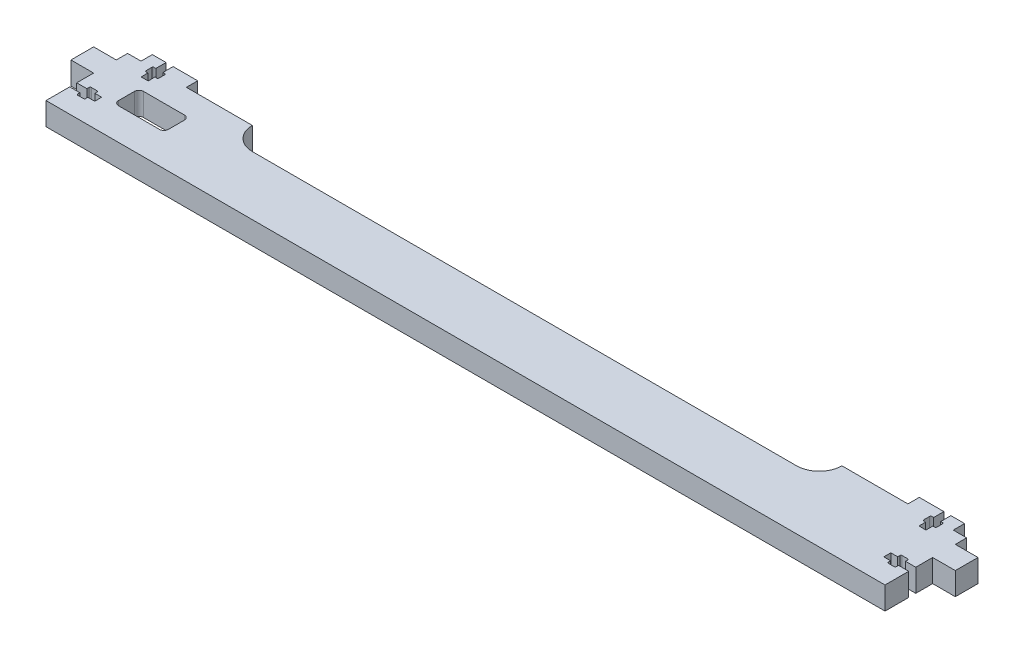
SolidWorks part; units mm, degrees
ref_plane "Front Plane" through (0, 0, 0) normal (0, 0, 1) x (1, 0, 0)
ref_plane "Top Plane" through (0, 0, 0) normal (0, 1, 0) x (1, 0, 0)
ref_plane "Right Plane" through (0, 0, 0) normal (1, 0, 0) x (0, 0, -1)
sketch "Sketch1" plane through (0, 0, 0) normal (0, 1, 0) x (1, 0, 0)
  line L0 (0, 18) -> (0, -18) construction
  line L1 (-185, 18) -> (0, 18)
  line L2 (-185, 18) -> (-185, 13)
  line L3 (-185, -18) -> (0, -18)
  line L4 (0, 18) -> (0, -18)
  line L5 (-185, 18) -> (0, 0) construction
  line L6 (-185, -18) -> (0, 0) construction
  line L7 (-185, 13) -> (-195, 13)
  line L8 (-195, 13) -> (-195, 3)
  line L9 (-195, 3) -> (-185, 3)
  line L10 (-185, 3) -> (-185, -18)
  point P0 (0, 0)
  dimension "D6" = 10
  dimension "D7" = 10
  dimension "D1" = 185
  dimension "D2" = 36
  dimension "D4" = 5
  dimension "D9" = 18
extrude "MainShape" add sketch "Sketch1" along normal blind 10
sketch "Sketch15" plane through (0, 10, 0) normal (0, 1, 0) x (1, 0, 0)
  line L0 (-185, 18) -> (0, 18) construction
  line L1 (-159.1, 23) -> (-179.1, 23)
  line L2 (-159.1, 23) -> (-159.1, 13)
  line L3 (-159.1, 13) -> (-179.1, 13)
  line L4 (-179.1, 23) -> (-179.1, 13)
  line L5 (-159.1, 23) -> (-179.1, 13) construction
  line L6 (-159.1, 13) -> (-179.1, 23) construction
  line L7 (-185, 18) -> (-185, 13) construction
  point P0 (-169.1, 18)
  dimension "D1" = 20
  dimension "D2" = 5
  dimension "D3" = 15.9
extrude "Boss-Extrude4" add sketch "Sketch15" against normal through all
sketch "Sketch2" plane through (0, 10, 0) normal (0, 1, 0) x (1, 0, 0)
  line L0 (-171.5, 23) -> (-171.5, 12) construction
  line L2 (-173.05, 23) -> (-173.05, 18.5)
  line L3 (-173.05, 18.5) -> (-173.85, 18.5)
  line L4 (-174.35, 18) -> (-174.35, 15.5)
  line L5 (-173.85, 15) -> (-173.05, 15)
  line L6 (-173.05, 15) -> (-173.05, 12)
  line L7 (-173.05, 12) -> (-169.95, 12)
  line L8 (-185, 18) -> (-185, 13) construction
  line L9 (-173.05, 23) -> (-169.95, 23)
  line L10 (-169.95, 15) -> (-169.95, 12)
  line L11 (-169.15, 15) -> (-169.95, 15)
  line L12 (-168.65, 18) -> (-168.65, 15.5)
  line L13 (-169.95, 18.5) -> (-169.15, 18.5)
  line L14 (-169.95, 23) -> (-169.95, 18.5)
  line L16 (-185, -6) -> (-174, -6) construction
  line L17 (-159.1, 23) -> (-179.1, 23) construction
  line L50 (-185, 3) -> (-185, -18) construction
  line L51 (-174, -7.55) -> (-174, -4.45)
  line L52 (-174, -4.45) -> (-177, -4.45)
  line L53 (-177, -4.45) -> (-177, -3.5)
  line L54 (-177.5, -3) -> (-180, -3)
  line L55 (-180.5, -3.5) -> (-180.5, -4.45)
  line L56 (-180.5, -4.45) -> (-185, -4.45)
  line L57 (-185, -4.45) -> (-185, -7.55)
  line L58 (-195, 13) -> (-195, 3) construction
  line L59 (-180.5, -7.55) -> (-185, -7.55)
  line L60 (-180.5, -8.5) -> (-180.5, -7.55)
  line L61 (-177.5, -9) -> (-180, -9)
  line L62 (-177, -7.55) -> (-177, -8.5)
  line L63 (-174, -7.55) -> (-177, -7.55)
  arc A0 (-174.35, 15.5) -> (-173.85, 15) centre (-173.85, 15.5) ccw
  arc A1 (-173.85, 18.5) -> (-174.35, 18) centre (-173.85, 18) ccw
  arc A2 (-169.15, 18.5) -> (-168.65, 18) centre (-169.15, 18) cw
  arc A3 (-168.65, 15.5) -> (-169.15, 15) centre (-169.15, 15.5) cw
  arc A16 (-177, -3.5) -> (-177.5, -3) centre (-177.5, -3.5) ccw
  arc A17 (-180, -3) -> (-180.5, -3.5) centre (-180, -3.5) ccw
  arc A18 (-180, -9) -> (-180.5, -8.5) centre (-180, -8.5) cw
  arc A19 (-177, -8.5) -> (-177.5, -9) centre (-177.5, -8.5) cw
  point P14 (-174.35, 15)
  point P17 (-174.35, 18.5)
  point P28 (-168.65, 18.5)
  point P29 (-168.65, 15)
  point P34 (-195, 8)
  point P45 (-177, -3)
  point P48 (-180.5, -3)
  dimension "D8" = 0.5
  dimension "D16" = 0.5
  dimension "D1" = 11
  dimension "D2" = 1.55
  dimension "D3" = 1.55
  dimension "D5" = 2.85
  dimension "D6" = 3.5
  dimension "D7" = 13.5
  dimension "D9" = 11
  dimension "D10" = 8
  dimension "D11" = 3.5
  dimension "D12" = 3
  dimension "D13" = 1.55
  dimension "D14" = 1.55
  dimension "D15" = 14
  dimension "D4" = 8
extrude "ScrewSlots" cut sketch "Sketch2" against normal through all
mirror "Mirror1" about plane through (0, 0, 0) normal (1, 0, 0) of "Boss-Extrude4", "ScrewSlots", "MainShape"
sketch "Sketch6" plane through (0, 10, 0) normal (0, 1, 0) x (1, 0, 0)
  line L0 (0, -18) -> (0, -48) construction
  line L2 (-185, -18) -> (185, -18) construction
  line L3 (90, -48) -> (-90, -48)
  line L4 (-90, -48) -> (-120, -18)
  line L5 (90, -48) -> (120, -18)
  line L6 (-120, -18) -> (120, -18)
  dimension "D1" = 135
  dimension "D2" = 30
  dimension "D3" = 90
extrude "Boss-Extrude1" [suppressed] add sketch "Sketch6" against normal through all
sketch "Sketch8" plane through (0, 10, 0) normal (0, 1, 0) x (1, 0, 0)
  line L0 (-71.5, 4.8833) -> (-77.5, 4.8833) construction
  line L1 (-77, -1.6167) -> (-72, -1.6167)
  line L2 (-78, -0.6167) -> (-78, 4.3833)
  line L3 (-77, 5.3833) -> (-72, 5.3833)
  line L4 (-71, -0.6167) -> (-71, 4.3833)
  line L5 (-78, -1.6167) -> (-71, 5.3833) construction
  line L6 (-78, 5.3833) -> (-71, -1.6167) construction
  line L7 (-71.5, -1.1167) -> (-71.5, 4.8833) construction
  circle A0 centre (-74.5, -34.7667) radius 6.5
  circle A1 centre (-74.5, -15.8167) radius 5.5
  arc A2 (-77, -1.6167) -> (-78, -0.6167) centre (-77, -0.6167) cw
  circle A3 centre (-74.5, -34.7667) radius 6 construction
  circle A4 centre (-74.5, -15.8167) radius 3.5 construction
  arc A5 (-72, -1.6167) -> (-71, -0.6167) centre (-72, -0.6167) ccw
  arc A6 (-72, 5.3833) -> (-71, 4.3833) centre (-72, 4.3833) cw
  arc A7 (-78, 4.3833) -> (-77, 5.3833) centre (-77, 4.3833) cw
  point P6 (-74.5, 1.8833)
  dimension "D1" = 0.5
  dimension "D2" = 2
  dimension "D3" = 0.5
  dimension "D5" = 1
  dimension "D4" = 0.5
extrude "Cut-Extrude2" [suppressed] cut sketch "Sketch8" against normal through all
sketch "Sketch7" plane through (0, 10, 0) normal (0, 1, 0) x (1, 0, 0)
  circle A0 centre (60.5, -43.0167) radius 1.45
  circle A1 centre (-84.5, -43.0167) radius 1.45
  circle A2 centre (-84.5, 6.4833) radius 1.45
  circle A3 centre (60.5, 6.4833) radius 1.45
  dimension "D1" = 2.9
  dimension "D2" = 2.9
  dimension "D3" = 2.9
  dimension "D4" = 2.9
extrude "Cut-Extrude1" [suppressed] cut sketch "Sketch7" against normal through all
sketch "Sketch9" plane through (0, 10, 0) normal (0, 1, 0) x (1, 0, 0)
  line L0 (0, 7.2333) -> (0, -32.7667) construction
  line L1 (48.5, 7.2333) -> (-48.5, 7.2333) construction
  line L2 (-48.5, -32.7667) -> (48.5, -32.7667) construction
  line L3 (-48.5, -12.7667) -> (48.5, -12.7667) construction
  line L4 (-48.5, 7.2333) -> (-48.5, -32.7667) construction
  line L5 (48.5, -32.7667) -> (48.5, 7.2333) construction
  line L7 (-49, -33.2667) -> (49, -33.2667)
  line L8 (-49, -33.2667) -> (-49, 7.7333)
  line L9 (-49, 7.7333) -> (49, 7.7333)
  line L10 (49, -33.2667) -> (49, 7.7333)
  line L11 (-49, -33.2667) -> (49, 7.7333) construction
  line L12 (-49, 7.7333) -> (49, -33.2667) construction
  point P12 (0, -12.7667)
  dimension "D1" = 0.5
  dimension "D2" = 0.5
extrude "Cut-Extrude3" [suppressed] cut sketch "Sketch9" against normal through all and the other way through all
sketch "Sketch10" plane through (0, 10, 0) normal (0, 1, 0) x (1, 0, 0)
  line L0 (20, -39.2667) -> (20, -40.7667) construction
  line L1 (40, -39.2667) -> (0, -39.2667) construction
  line L2 (0, -40.7667) -> (40, -40.7667) construction
  line L3 (0, -40.0167) -> (40, -40.0167) construction
  line L4 (0, -39.2667) -> (0, -40.7667) construction
  line L5 (40, -40.7667) -> (40, -39.2667) construction
  line L7 (-0.2, -40.9667) -> (40.2, -40.9667)
  line L8 (-0.2, -40.9667) -> (-0.2, -39.0667)
  line L9 (-0.2, -39.0667) -> (40.2, -39.0667)
  line L10 (40.2, -40.9667) -> (40.2, -39.0667)
  line L11 (-0.2, -40.9667) -> (40.2, -39.0667) construction
  line L12 (-0.2, -39.0667) -> (40.2, -40.9667) construction
  point P12 (20, -40.0167)
  dimension "D1" = 0.2
  dimension "D2" = 0.2
extrude "Cut-Extrude4" [suppressed] cut sketch "Sketch10" against normal through all
sketch "Sketch12" [suppressed] plane through (0, 0, 0) normal (0, -1, 0) x (-1, 0, 0)
  line L1 (81.4, -9.8167) -> (67.6, -9.8167)
  line L2 (81.4, -9.8167) -> (81.4, -21.8167)
  line L3 (81.4, -21.8167) -> (67.6, -21.8167)
  line L4 (67.6, -9.8167) -> (67.6, -21.8167)
  line L5 (81.4, -9.8167) -> (67.6, -21.8167) construction
  line L6 (81.4, -21.8167) -> (67.6, -9.8167) construction
  point P0 (74.5, -15.8167)
  dimension "D1" = 13.8
  dimension "D2" = 12
extrude "PotentiometerAdjustment" [suppressed] cut sketch "Sketch12" against normal through all
sketch "Sketch11" plane through (0, 0, 0) normal (0, -1, 0) x (1, 0, 0)
  line L1 (-149, -7) -> (-167, -7)
  line L2 (-147, -5) -> (-147, 2)
  line L3 (-149, 4) -> (-167, 4)
  line L4 (-169, -5) -> (-169, 2)
  line L5 (-147, -7) -> (-169, 4) construction
  line L6 (-147, 4) -> (-169, -7) construction
  line L7 (173.05, -12) -> (169.95, -12) construction
  line L8 (-174, 7.55) -> (-174, 4.45) construction
  arc A0 (-147, 2) -> (-149, 4) centre (-149, 2) ccw
  arc A1 (-167, 4) -> (-169, 2) centre (-167, 2) ccw
  arc A2 (-167, -7) -> (-169, -5) centre (-167, -5) cw
  arc A3 (-149, -7) -> (-147, -5) centre (-149, -5) ccw
  point P0 (-158, -1.5)
  dimension "D3" = 2
  dimension "D1" = 22
  dimension "D2" = 11
  dimension "D4" = 5
  dimension "D5" = 5
extrude "LCDCableCutout" cut sketch "Sketch11" against normal through all
sketch "Sketch13" plane through (0, 10, 0) normal (0, 1, 0) x (1, 0, 0)
  line L0 (0, 18) -> (0, -18) construction
  line L1 (-169.95, 18) -> (169.95, 18) construction
  line L2 (-185, -18) -> (185, -18) construction
  line L3 (120, 18) -> (-120, 18) construction
  line L4 (120, 8) -> (-120, 8)
  line L5 (120, 28) -> (-120, 28)
  arc A0 (120, 8) -> (120, 28) centre (120, 18) ccw
  arc A1 (-120, 28) -> (-120, 8) centre (-120, 18) ccw
  point P8 (0, 18)
  dimension "D2" = 120
  dimension "D1" = 10
extrude "Cut-Extrude5" cut sketch "Sketch13" against normal through all
sketch "Sketch14" plane through (0, 10, 0) normal (0, 1, 0) x (1, 0, 0)
  line L1 (-169.95, 18) -> (169.95, 18) construction
  line L3 (-156.5, 18) -> (-156.5, 28) construction
  line L4 (-161.5, 18) -> (-151.5, 18)
  line L5 (-161.5, 18) -> (-161.5, 28)
  line L6 (-161.5, 28) -> (-151.5, 28)
  line L7 (-151.5, 18) -> (-151.5, 28)
  line L8 (-173.05, 12) -> (-169.95, 12) construction
  line L9 (154, 18) -> (154, 28) construction
  line L10 (149, 18) -> (149, 28)
  line L11 (159, 28) -> (149, 28)
  line L12 (159, 18) -> (159, 28)
  line L13 (159, 18) -> (149, 18)
  point P12 (-171.5, 12)
  dimension "D1" = 10
  dimension "D2" = 10
  dimension "D3" = 15
extrude "Boss-Extrude3" [suppressed] add sketch "Sketch14" against normal through all
equation "\"Y-ROD-SPACING\"=75"
equation "\"Y-BED-OFFSET\"=2"
equation "\"Y-BED-ROD-INSET\"=3.5"
equation "\"T-SLOT-NUT-FILLET-RADIUS\"=0.5"
equation "\"T-SLOT-SCREW-SHAFT-RADIUS\"=1.55"
equation "\"T-SLOT-SCREW-SHAFT-CUTOUT-LENGTH\"=11"
equation "\"T-SLOT-NUT-DEPTH\"=3.5"
equation "\"T-SLOT-NUT-WIDTH\"=2.85"
equation "\"T-SLOT-NUT-END-DISTANCE\"=8"
equation "\"ACRYLIC-TAB-CUTOUT-SIZE\"=\"ACRYLIC-THICKNESS\"+\"ACRYLIC-TAB-TOLERANCE\"*2"
equation "\"ACRYLIC-M3-HOLE\"=2.9"
equation "\"SMOOTHROD-CAP-SCREW-DISTANCE\"=20"
equation "\"D2@Sketch2\"=\"T-SLOT-SCREW-SHAFT-RADIUS\""
equation "\"D1@Sketch2\"=\"T-SLOT-SCREW-SHAFT-CUTOUT-LENGTH\""
equation "\"D6@Sketch2\"=\"T-SLOT-NUT-DEPTH\""
equation "\"D5@Sketch2\"=\"T-SLOT-NUT-WIDTH\""
equation "\"D3@Sketch2\"=\"T-SLOT-SCREW-SHAFT-RADIUS\""
equation "\"D8@Sketch2\"=\"T-SLOT-NUT-FILLET-RADIUS\""
equation "\"D4@Sketch2\"=\"T-SLOT-NUT-END-DISTANCE\""
equation "\"D11@Sketch2\"=\"T-SLOT-NUT-DEPTH\""
equation "\"D10@Sketch2\"=\"T-SLOT-NUT-END-DISTANCE\""
equation "\"D13@Sketch2\"=\"T-SLOT-SCREW-SHAFT-RADIUS\""
equation "\"D14@Sketch2\"=\"T-SLOT-SCREW-SHAFT-RADIUS\""
equation "\"D16@Sketch2\"=\"T-SLOT-NUT-FILLET-RADIUS\""
equation "\"D9@Sketch2\"=\"T-SLOT-SCREW-SHAFT-CUTOUT-LENGTH\""
equation "\"ACRYLIC-TAB-WIDTH\"=\"ACRYLIC-THICKNESS\""
equation "\"D6@Sketch1\"=\"ACRYLIC-TAB-WIDTH\""
equation "\"D7@Sketch1\"=\"ACRYLIC-TAB-WIDTH\""
equation "\"FRAME-WIDTH-INNER\"=370"
equation "\"D1@Sketch1\"=\"FRAME-WIDTH-INNER\"/2"
equation "\"X-ROD-SPACING\"=45"
equation "\"Z-ROD-SPACING\"=17.5"
equation "\"ACRYLIC-THICKNESS\"=10"
equation "\"ACRYLIC-THICKNESS2\"=4.5"
equation "\"NEMA17-HOLE-SPACING\"=31"
equation "\"NEMA17-CENTRAL-CUTOUT\"=22.5"
equation "\"Z-BRACKET-REACH\"=57"
equation "\"TOP-BRACKET-SPACING\"=40"
equation "\"SMOOTHROD-X-LENGTH\"=350"
equation "\"SMOOTHROD-Y-LENGTH\"=350"
equation "\"SMOOTHROD-Z-LENGTH\"=350"
equation "\"SMOOTHROD-TIGHTENING-HEADROOM\"=.25"
equation "\"LEADSCREW-Z-LENGTH\"=300"
equation "\"SCREW-LENGTH-FRAME\"=\"ACRYLIC-THICKNESS\" + 10"
equation "\"SCREW-HEAD-RADIUS\"=6"
equation "\"PRINTED-X-SMOOTHROD-DIAMETER\"=8.8"
equation "\"PRINTED-X-SMOOTHROD-CUTOUT\"=10"
equation "\"PRINTED-X-BASE-HEIGHT\"=10"
equation "\"PRINTED-LM8UU-CUTOUT-SIZE\"=15.5"
equation "\"PRINTED-LM8UU-CUTOUT-LENGTH\"=24.5"
equation "\"PRINTED-X-IDLER-HEIGHT\"=16"
equation "\"PSU-MOUNTING-WIDTH\"=95"
equation "\"PSU-MOUNTING-HEIGHT\"=177"
equation "\"D1@MainShape\"=\"ACRYLIC-THICKNESS\""
equation "\"Y-BELT-TO-ROD-DISTANCE\"=20"
equation "\"SPOOL-HOLDER-ROD-SPACING\"=150"
equation "\"Z-ROD-INSET\"=13.5"
equation "\"D7@Sketch2\"=\"Z-ROD-INSET\""
equation "\"D1@Sketch7\"=\"ACRYLIC-M3-HOLE\""
equation "\"D2@Sketch7\"=\"ACRYLIC-M3-HOLE\""
equation "\"D3@Sketch7\"=\"ACRYLIC-M3-HOLE\""
equation "\"D4@Sketch7\"=\"ACRYLIC-M3-HOLE\""
equation "\"Y-BED-SCREW-SPACING\"=209"
equation "\"Y-BED-SCREW-CUTOUT-SLOT-HEIGHT\"=2"
equation "\"ACRYLIC-TAB-TOLERANCE\"=-.05"
equation "\"SCREW-LENGTH-MOTOR\"=\"ACRYLIC-THICKNESS\" + 5"
equation "\"SCREW-LENGTH-EXTRUDER\"=28"
equation "\"PRINTED-M3-HOLE\"=3.5"
equation "\"PRINTED-M3-NUT-AF\"=6.25"
equation "\"ACRYLIC-X-CARRIAGE-WIDTH\"=55"
equation "\"ACRYLIC-X-CARRIAGE-HEIGHT\"=75"
equation "\"ACRYLIC-X-CARRIAGE-LM8UU-CUTOUT-WIDTH\"=24.25"
equation "\"ACRYLIC-X-CARRIAGE-LM8UU-CUTOUT-HEIGHT\"=11.0"
equation "\"ACRYLIC-X-CARRIAGE-SCREW-SPACING-X\"=15"
equation "\"ACRYLIC-X-CARRIAGE-SCREW-SPACING-Y\"=33"
equation "\"ACRYLIC-X-CARRIAGE-CENTER-TAB-SPACING\"=14"
equation "\"ACRYLIC-X-CARRIAGE-EXTRUDER-OFFSET\"=26"
equation "\"ACRYLIC-X-CARRIAGE-EXTRUDER-ANGLE\"=90"
equation "\"ACRYLIC-X-CARRIAGE-EXTRUDER-SHELF-DEPTH\"=\"ACRYLIC-X-CARRIAGE-EXTRUDER-OFFSET\" + 28"
equation "\"ACRYLIC-X-CARRIAGE-EXTRUDER-BRACE-SPACING\"=23"
equation "\"ACRYLIC-X-CARRIAGE-EXTRUDER-BRACE-TAB-OFFSET\"=20"
equation "\"ACRYLIC-X-CARRIAGE-EXTRUDER-BRACE-HEIGHT\"=35"
equation "\"ACRYLIC-X-CARRIAGE-EXTRUDER-BRACE-SCREW-SPACING\"=22"
equation "\"ACRYLIC-X-CARRIAGE-DUAL-WIDTH-MULTIPLIER\"=1.65"
equation "\"ACRYLIC-X-CARRIAGE-DUAL-HOTEND-SPACING\"=42"
equation "\"ACRYLIC-X-CARRIAGE-DUAL-WIDTH\"=75"
equation "\"ACRYLIC-X-CARRIAGE-DUAL-HOTEND-SEPARATION\"=36"
equation "\"ACRYLIC-X-CARRIAGE-DUAL-MOUNT-PLATE-DEPTH\"=75"
equation "\"ACRYLIC-X-CARRIAGE-DUAL-MOUNT-BRACE-WIDTH\"=33"
equation "\"ACRYLIC-X-CARRIAGE-DUAL-MOUNT-SCREW-WIDTH\"=40"
equation "\"BLOWER-FAN-WIDTH\"=15"
equation "\"D1@Sketch14\"=\"ACRYLIC-TAB-WIDTH\""
equation "\"D2@Sketch14\"=\"ACRYLIC-THICKNESS\""
equation "\"D3@Sketch15\"=\"Z-ROD-INSET\"+2.4"
